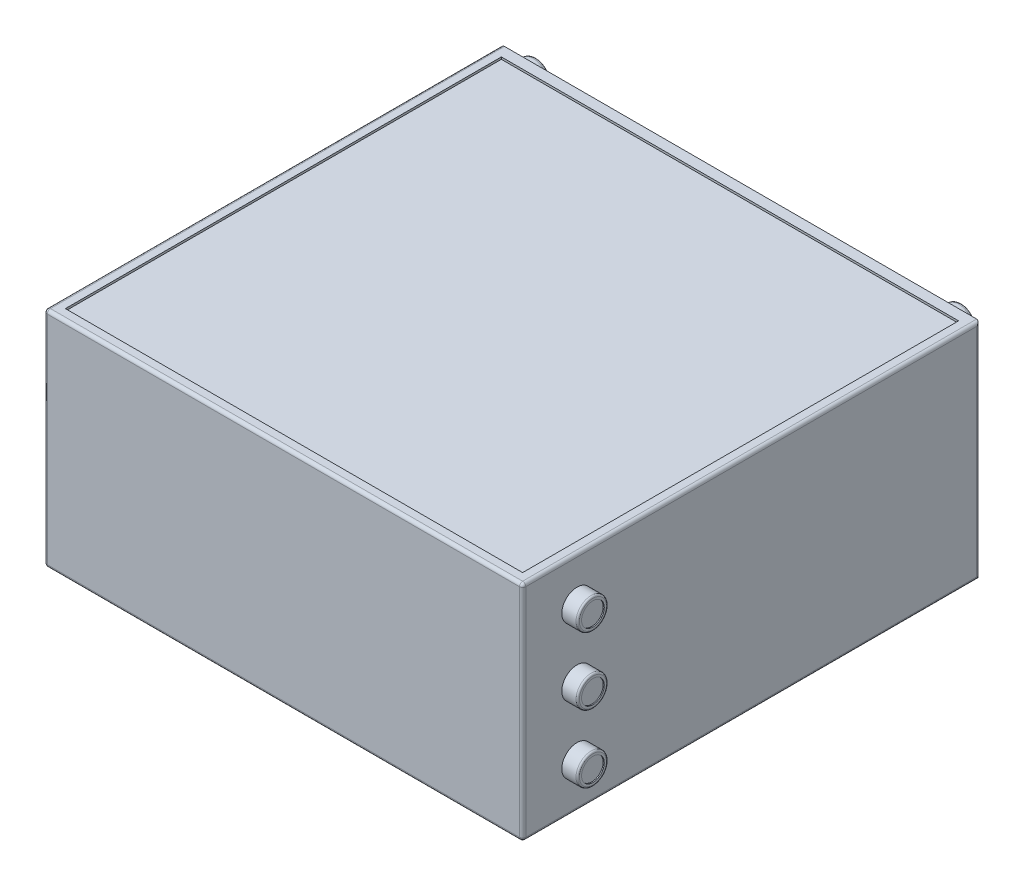
SolidWorks part; units mm, degrees
ref_plane "Front Plane" through (0, 0, 0) normal (0, 0, 1) x (1, 0, 0)
ref_plane "Top Plane" through (0, 0, 0) normal (0, 1, 0) x (1, 0, 0)
ref_plane "Right Plane" through (0, 0, 0) normal (1, 0, 0) x (0, 0, -1)
sketch "Layer 1" plane through (0, 0, 0) normal (0, 0, 1) x (1, 0, 0)
  line L0 (1757.8602, -116.9002) -> (2207.8602, -116.9002)
  line L1 (2207.8602, -116.9002) -> (2207.8602, 93.0998)
  line L2 (2207.8602, 93.0998) -> (1757.8602, 93.0998)
  line L3 (1757.8602, 93.0998) -> (1757.8602, -116.9002)
  ellipse E0 centre (1782.8602, -74.4002) end of major axis (1782.8602, -71.4002) minor radius 3
  ellipse E1 centre (2182.8602, -74.4002) end of major axis (2179.8602, -74.4002) minor radius 3
  ellipse E2 centre (1782.8602, 50.5998) end of major axis (1782.8602, 53.5998) minor radius 3
  ellipse E3 centre (2182.8602, 50.5998) end of major axis (2179.8602, 50.5998) minor radius 3
sketch "Sketch2" plane through (0, 0, 0) normal (0, 0, 1) x (1, 0, 0)
  line L0 (1757.8602, 93.0998) -> (1757.8602, -116.9002) construction
  line L1 (1757.8602, 93.0998) -> (1757.8602, -116.9002)
  line L2 (2207.8602, 93.0998) -> (1757.8602, 93.0998) construction
  line L3 (2207.8602, 93.0998) -> (1757.8602, 93.0998)
  line L4 (2207.8602, -116.9002) -> (2207.8602, 93.0998) construction
  line L5 (2207.8602, -116.9002) -> (2207.8602, 93.0998)
  line L6 (1757.8602, -116.9002) -> (2207.8602, -116.9002) construction
  line L7 (1757.8602, -116.9002) -> (2207.8602, -116.9002)
extrude "Boss-Extrude1" add sketch "Sketch2" along normal blind 430
ref_plane "Plane1" through (0, -11.9002, 0) normal (0, -1, 0) x (-1, 0, 0)
sketch "Sketch3" plane through (0, -116.9002, 0) normal (0, -1, 0) x (1, 0, 0)
  line L0 (1767.8602, 10) -> (2197.8602, 10)
  line L1 (2197.8602, 10) -> (2197.8602, 420)
  line L2 (2197.8602, 420) -> (1767.8602, 420)
  line L3 (1767.8602, 420) -> (1767.8602, 10)
  line L4 (1757.8602, 0) -> (2207.8602, 0)
  line L5 (2207.8602, 0) -> (2207.8602, 430)
  line L6 (2207.8602, 430) -> (1757.8602, 430)
  line L7 (1757.8602, 430) -> (1757.8602, 0)
  line L8 (1757.8602, 0) -> (2207.8602, 0) construction
  line L9 (2207.8602, 0) -> (2207.8602, 430) construction
  line L10 (2207.8602, 430) -> (1757.8602, 430) construction
  line L11 (1757.8602, 430) -> (1757.8602, 0) construction
  dimension "D1" = 0
  dimension "D2" = 10
extrude "Cut-Extrude1" cut sketch "Sketch3" against normal blind 2
mirror "Mirror1" about plane through (0, -11.9002, 0) normal (0, -1, 0) of "Cut-Extrude1"
fillet "Fillet1" radius 3 10 edges at (2207.8602, -116.9002, 215) (2207.8602, 93.0998, 215) (2207.8602, -11.9002, 0) (1757.8602, 93.0998, 215) (1757.8602, -116.9002, 215) (1757.8602, -11.9002, 0) (2207.8602, -11.9002, 430) (1982.8602, -116.9002, 430) (1757.8602, -11.9002, 430) (1982.8602, 93.0998, 430)
sketch "Sketch4" plane through (2207.8602, 0, 0) normal (1, 0, 0) x (0, 0, -1)
  line L0 (-430, -11.9002) -> (0, -11.9002) construction
  line L1 (-430, -113.9002) -> (-430, 90.0998) construction
  line L2 (0, 93.0998) -> (0, -116.9002) construction
  line L3 (-378.8999, 51.4054) -> (-378.8999, -75.2058) construction
  circle A0 centre (-378.8999, 51.4054) radius 14.283
  circle A1 centre (-378.8999, -75.2058) radius 14.283
  circle A2 centre (-378.8999, -11.9002) radius 14.283
extrude "Boss-Extrude2" add sketch "Sketch4" along normal blind 15 separate body
fillet "Fillet2" radius 1.6 1 edges at (2222.8602, -75.2058, 393.1829)
fillet "Fillet3" radius 1.6 1 edges at (2222.8602, -11.9002, 364.6169)
fillet "Fillet4" radius 1.6 1 edges at (2222.8602, 51.4054, 364.6169)
sketch "Sketch5" plane through (2222.8602, 0, 0) normal (1, 0, 0) x (0, 0, -1)
  circle A0 centre (-378.8999, -75.2058) radius 12.683 construction
  circle A1 centre (-378.8999, -11.9002) radius 12.683 construction
  circle A2 centre (-378.8999, 51.4054) radius 12.683 construction
  circle A3 centre (-378.8999, -75.2058) radius 12.683 construction
  circle A4 centre (-378.8999, -11.9002) radius 12.683 construction
  circle A5 centre (-378.8999, 51.4054) radius 12.683 construction
  circle A6 centre (-378.8999, 51.4054) radius 10.683
  circle A7 centre (-378.8999, -11.9002) radius 10.683
  circle A8 centre (-378.8999, -75.2058) radius 10.683
  dimension "D1" = 2
  dimension "D2" = 2
  dimension "D3" = 2
extrude "Cut-Extrude2" cut sketch "Sketch5" against normal blind 1
sketch "Sketch6" plane through (0, 0, 0) normal (0, 0, -1) x (-1, 0, 0)
  circle A0 centre (-2182.8602, 50.5998) radius 3 construction
  circle A1 centre (-2182.8602, 50.5998) radius 3
  circle A2 centre (-1782.8602, 50.5998) radius 3 construction
  circle A3 centre (-1782.8602, 50.5998) radius 3
  circle A4 centre (-1782.8602, -74.4002) radius 3 construction
  circle A5 centre (-1782.8602, -74.4002) radius 3
  circle A6 centre (-2182.8602, -74.4002) radius 3 construction
  circle A7 centre (-2182.8602, -74.4002) radius 3
extrude "Cut-Extrude3" cut sketch "Sketch6" against normal blind 10
sketch "Sketch7" plane through (0, 0, 0) normal (0, 0, -1) x (-1, 0, 0)
  line L0 (-2204.8602, -11.9002) -> (-1760.8602, -11.9002) construction
  line L1 (-2204.8602, 93.0998) -> (-2204.8602, -116.9002) construction
  line L2 (-1760.8602, -116.9002) -> (-1760.8602, 93.0998) construction
  line L3 (-1982.8602, 93.0998) -> (-1982.8602, -116.9002) construction
  line L4 (-2204.8602, 93.0998) -> (-1760.8602, 93.0998) construction
  line L5 (-1760.8602, -116.9002) -> (-2204.8602, -116.9002) construction
  circle A0 centre (-2182.8602, 77.4029) radius 14.3651
  circle A1 centre (-1782.8602, 77.4029) radius 14.3651
  circle A2 centre (-1782.8602, -101.2033) radius 14.3651
  circle A3 centre (-2182.8602, -101.2033) radius 14.3651
extrude "Boss-Extrude3" add sketch "Sketch7" along normal blind 8 separate body
fillet "Fillet5" radius 3 1 edges at (2197.2253, -101.2033, -8)
fillet "Fillet6" radius 3 1 edges at (2168.4951, 77.4029, -8)
fillet "Fillet7" radius 3 1 edges at (1797.2253, 77.4029, -8)
fillet "Fillet8" radius 3 1 edges at (1768.4951, -101.2033, -8)
